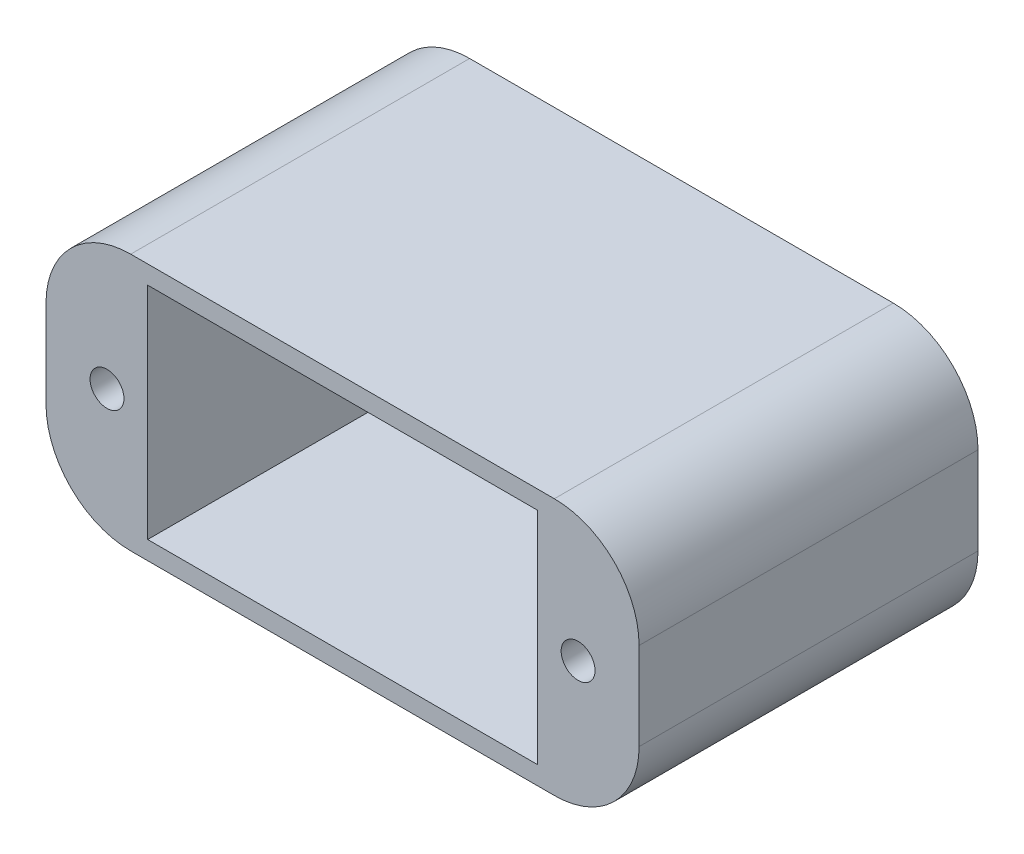
SolidWorks part; units mm, degrees
ref_plane "Front Plane" through (0, 0, 0) normal (0, 0, 1) x (1, 0, 0)
ref_plane "Top Plane" through (0, 0, 0) normal (0, 1, 0) x (1, 0, 0)
ref_plane "Right Plane" through (0, 0, 0) normal (1, 0, 0) x (0, 0, -1)
sketch "Sketch1" plane through (0, 0, 0) normal (0, 0, 1) x (1, 0, 0)
  line L1 (-17.5, -12.5) -> (17.5, -12.5)
  line L2 (-17.5, -12.5) -> (-17.5, 12.5)
  line L3 (-17.5, 12.5) -> (17.5, 12.5)
  line L4 (17.5, -12.5) -> (17.5, 12.5)
  line L5 (-17.5, -12.5) -> (17.5, 12.5) construction
  line L6 (-17.5, 12.5) -> (17.5, -12.5) construction
  point P0 (0, 0)
  dimension "D1" = 35
  dimension "D2" = 25
extrude "Boss-Extrude1" add sketch "Sketch1" along normal mid plane 20
sketch "Sketch2" plane through (0, 0, 10) normal (0, 0, 1) x (1, 0, 0)
  line L0 (-17.5, 0) -> (17.5, 0) construction
  line L1 (-17.5, 12.5) -> (-17.5, -12.5) construction
  line L2 (17.5, -12.5) -> (17.5, 12.5) construction
  line L3 (17.5, 12.5) -> (-17.5, 12.5) construction
  line L4 (0, 12.5) -> (0, -12.5) construction
  line L5 (-17.5, -12.5) -> (17.5, -12.5) construction
  line L7 (-11.5, -6.5) -> (11.5, -6.5)
  line L8 (-11.5, -6.5) -> (-11.5, 6.5)
  line L9 (-11.5, 6.5) -> (11.5, 6.5)
  line L10 (11.5, -6.5) -> (11.5, 6.5)
  line L11 (-11.5, -6.5) -> (11.5, 6.5) construction
  line L12 (-11.5, 6.5) -> (11.5, -6.5) construction
  point P12 (0, 0)
  dimension "D1" = 23
  dimension "D2" = 13
extrude "Cut-Extrude1" cut sketch "Sketch2" against normal blind 16
sketch "Sketch3" plane through (0, 0, 10) normal (0, 0, 1) x (1, 0, 0)
  line L0 (-17.5, 0) -> (17.5, 0) construction
  line L1 (-17.5, 12.5) -> (-17.5, -12.5) construction
  line L2 (17.5, -12.5) -> (17.5, 12.5) construction
  line L3 (17.5, 12.5) -> (-17.5, 12.5) construction
  line L4 (0, 12.5) -> (0, -12.5) construction
  line L5 (-17.5, -12.5) -> (17.5, -12.5) construction
  line L6 (-11.5, 6.5) -> (-11.5, -6.5) construction
  circle A0 centre (-13.9, 0) radius 1
  circle A1 centre (13.9, 0) radius 1
  point P12 (-11.5, 0)
  point P13 (-13.9, 0)
  dimension "D2" = 2
  dimension "D1" = 2.4
sketch "Sketch4" plane through (0, 0, 10) normal (0, 0, 1) x (1, 0, 0)
  line L0 (17.5, -12.5) -> (17.5, 12.5) construction
  line L1 (-17.5, 12.5) -> (17.5, 12.5)
  line L2 (-17.5, 12.5) -> (-17.5, 7.5843)
  line L3 (-17.5, 7.5843) -> (17.5, 7.5843)
  line L4 (17.5, 12.5) -> (17.5, 7.5843)
  line L5 (-17.5, 0) -> (17.5, 0) construction
  line L6 (-17.5, 12.5) -> (-17.5, -12.5) construction
  line L7 (-17.5, -7.5843) -> (17.5, -7.5843)
  line L8 (17.5, -12.5) -> (17.5, -7.5843)
  line L9 (-17.5, -12.5) -> (17.5, -12.5)
  line L10 (-17.5, -12.5) -> (-17.5, -7.5843)
extrude "Cut-Extrude3" cut sketch "Sketch4" against normal up to next
fillet "Fillet2" radius 5 1 edges at (17.5, -7.5843, 0)
fillet "Fillet3" radius 5 1 edges at (17.5, 7.5843, 0)
fillet "Fillet4" radius 5 1 edges at (-17.5, 7.5843, 0)
fillet "Fillet5" radius 5 1 edges at (-17.5, -7.5843, 0)
extrude "Cut-Extrude4" cut sketch "Sketch3" against normal up to next
